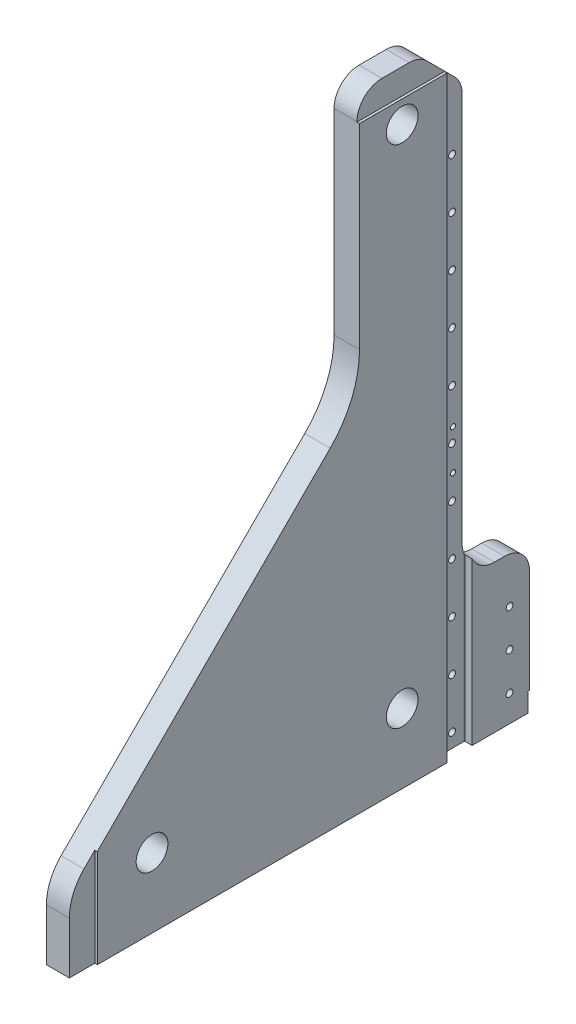
SolidWorks part; units mm, degrees
material "Low Carbon Steel"
ref_plane "Front Plane" through (0, 0, 0) normal (0, 0, 1) x (1, 0, 0)
ref_plane "Top Plane" through (0, 0, 0) normal (0, 1, 0) x (1, 0, 0)
ref_plane "Right Plane" through (0, 0, 0) normal (1, 0, 0) x (0, 0, -1)
sketch "Sketch1" plane through (0, 0, 0) normal (1, 0, 0) x (0, 0, -1)
  line L0 (0, 350) -> (0, 1129.2893)
  line L1 (-120.7107, 1250) -> (-175, 1250)
  line L2 (-225, 1200) -> (-225, 807.8427)
  line L3 (-283.5786, 666.4214) -> (-770.7107, 179.2893)
  line L4 (-800, 108.5786) -> (-800, 0)
  line L5 (-85.3553, 1235.3553) -> (-14.6447, 1164.6447)
  line L6 (0, 0) -> (120, 0)
  line L7 (-800, 0) -> (0, 0)
  line L9 (50, 300) -> (70, 300)
  line L10 (120, 0) -> (120, 250)
  arc A0 (-770.7107, 179.2893) -> (-800, 108.5786) centre (-700, 108.5786) ccw
  arc A1 (-225, 807.8427) -> (-283.5786, 666.4214) centre (-425, 807.8427) cw
  arc A2 (0, 350) -> (50, 300) centre (50, 350) ccw
  arc A3 (70, 300) -> (120, 250) centre (70, 250) cw
  arc A4 (-14.6447, 1164.6447) -> (0, 1129.2893) centre (-50, 1129.2893) cw
  arc A5 (-85.3553, 1235.3553) -> (-120.7107, 1250) centre (-120.7107, 1200) ccw
  arc A6 (-175, 1250) -> (-225, 1200) centre (-175, 1200) ccw
  point P8 (-800, 150)
  point P12 (-225, 725)
  point P18 (0, 300)
  point P21 (120, 300)
  point P27 (-100, 1250)
  dimension "D6" = 100
  dimension "D7" = 200
  dimension "D10" = 50
  dimension "D13" = 50
  dimension "D1" = 45
  dimension "D2" = 125
  dimension "D3" = 150
  dimension "D4" = 575
  dimension "D5" = 225
  dimension "D8" = 120
  dimension "D9" = 300
  dimension "D11" = 920
  dimension "D12" = 1250
extrude "Boss-Extrude1" add sketch "Sketch1" along normal blind 50.8
sketch "Sketch2" plane through (0, 1250, 0) normal (0, 1, 0) x (1, 0, 0)
  line L1 (30.8, 5) -> (50.8, 5)
  line L2 (30.8, 5) -> (30.8, -50)
  line L3 (30.8, -50) -> (50.8, -50)
  line L4 (50.8, 5) -> (50.8, -50)
  line L5 (50.8, -120.7107) -> (50.8, -175) construction
  line L6 (50.8, 0) -> (0, 0) construction
  dimension "D1" = 50
  dimension "D2" = 20
  dimension "D3" = 5
extrude "Cut-Extrude1" cut sketch "Sketch2" against normal through all
sketch "Sketch3" plane through (0, 0, 800) normal (0, 0, -1) x (-1, 0, 0)
  line L0 (-50.8, 0) -> (-50.8, 1200) construction
  line L1 (0, 0) -> (-50.8, 0)
  line L2 (0, 0) -> (0, 5)
  line L3 (0, 5) -> (-50.8, 5)
  line L4 (-50.8, 0) -> (-50.8, 5)
  dimension "D1" = 5
extrude "Cut-Extrude2" cut sketch "Sketch3" along normal through all
sketch "Sketch5" plane through (50.8, 0, 0) normal (1, 0, 0) x (0, 0, -1)
  line L1 (5, 328.2055) -> (120, 328.2055)
  line L2 (5, 328.2055) -> (5, 5)
  line L3 (5, 5) -> (120, 5)
  line L4 (120, 328.2055) -> (120, 5)
extrude "Cut-Extrude5" cut sketch "Sketch5" against normal offset from surface (5 mm away) 15 up to face at (30.8, 597.6161, 14.6232)
sketch "Sketch6" plane through (30.8, 0, 0) normal (1, 0, 0) x (0, 0, -1)
  line L0 (0, 1129.2893) -> (0, 350) construction
  line L1 (-185, 595) -> (0, 595)
  line L2 (-185, 595) -> (-185, 445)
  line L3 (-185, 445) -> (0, 445)
  line L4 (0, 595) -> (0, 445)
  line L6 (-50, 5) -> (-800, 5) construction
  line L7 (-50, 5) -> (-50, 1200) construction
  dimension "D1" = 150
  dimension "D2" = 135
  dimension "D3" = 440
extrude "Cut-Extrude6" cut sketch "Sketch6" against normal through all from offset 27 offset against normal yes
fillet "Fillet1" radius 38.1 2 edges at (1.9, 445, 185) (1.9, 595, 185)
hole_wizard "M12 Tapped Hole1" positions "Sketch8" profile "Sketch7" tap size "M12" standard "Peddi DIN"
sketch "Sketch8" plane through (3.8, 0, 0) normal (-1, 0, 0) x (0, 0, 1)
  line L0 (18, 561) -> (150, 561) construction
  line L1 (150, 561) -> (150, 481) construction
  line L2 (150, 481) -> (18, 481) construction
  line L3 (18, 481) -> (18, 561) construction
  line L6 (-120, 5) -> (800, 5) construction
  line L7 (50, 5) -> (50, 1200) construction
  point P0 (150, 561)
  point P2 (18, 561)
  point P4 (18, 481)
  point P6 (150, 481)
  dimension "D1" = 132
  dimension "D2" = 80
  dimension "D3" = 32
  dimension "D4" = 476
sketch "Sketch7" plane through (3.8, 561, 150) normal (0, 1, 0) x (0, 0, 1)
  line L0 (0, 0) -> (0, 47.0544)
  line L1 (0, 47.0544) -> (5.1, 43.99)
  line L2 (5.1, 43.99) -> (5.1, 0)
  line L5 (5.1, 0) -> (0, 0)
  line L10 (0, 47.0544) -> (-5.1, 43.99) construction
  line L11 (0, -6.35) -> (0, 107.95) construction
  dimension "Tap Drill Dia." = 10.2
  dimension "Tap Drill Depth" = 43.99
  dimension "Drill Angle" = 118
cosmetic thread "Hole Thread1" parameters "D1"=30, "D2"=12
cosmetic thread "Hole Thread2" parameters "D1"=27, "D2"=12
cosmetic thread "Hole Thread3" parameters "D1"=27, "D2"=12
cosmetic thread "Hole Thread4" parameters "D1"=30, "D2"=12
sketch "Sketch9" plane through (3.8, 0, 0) normal (-1, 0, 0) x (0, 0, 1)
  line L0 (89, 544) -> (89, 498) construction
  line L1 (95, 544) -> (95, 498)
  line L2 (83, 544) -> (83, 498)
  line L3 (18, 561) -> (18, 481) construction
  line L4 (18, 521) -> (89, 521) construction
  arc A0 (95, 544) -> (83, 544) centre (89, 544) ccw
  arc A1 (83, 498) -> (95, 498) centre (89, 498) ccw
  point P2 (89, 521)
  dimension "D1" = 12
  dimension "D2" = 65
  dimension "D3" = 46
extrude "Cut-Extrude7" cut sketch "Sketch9" against normal blind 5.08
hole_wizard "CBORE for M12 Hex Socket Head Cap Screw1" positions "Sketch10" profile "Sketch11" counterbore size "M12" standard "Peddi DIN" end condition through all
sketch "Sketch10" plane through (0, 0, 0) normal (-1, 0, 0) x (0, 0, 1)
  line L0 (50, 5) -> (50, 1200) construction
  line L2 (-120, 5) -> (800, 5) construction
  line L4 (-80, 58) -> (-80, 133) construction
  line L5 (-80, 133) -> (-80, 208) construction
  line L7 (20, 33) -> (20, 133) construction
  line L8 (20, 133) -> (20, 233) construction
  line L9 (20, 233) -> (20, 333) construction
  line L10 (20, 333) -> (20, 433) construction
  line L12 (20, 433) -> (20, 533) construction
  line L13 (20, 533) -> (20, 633) construction
  line L14 (20, 633) -> (20, 733) construction
  line L15 (20, 733) -> (20, 833) construction
  line L16 (20, 833) -> (20, 933) construction
  line L17 (20, 933) -> (20, 1033) construction
  line L18 (20, 133) -> (-80, 133) construction
  point P0 (20, 33)
  point P10 (-80, 58)
  point P20 (-80, 133)
  point P21 (-80, 208)
  point P26 (20, 133)
  point P28 (20, 233)
  point P30 (20, 333)
  point P32 (20, 433)
  point P39 (20, 533)
  point P41 (20, 633)
  point P42 (20, 733)
  point P44 (20, 833)
  point P46 (20, 933)
  point P48 (20, 1033)
  dimension "D4" = 75
  dimension "D1" = 30
  dimension "D2" = 28
  dimension "D3" = 100
  dimension "D5" = 100
sketch "Sketch11" plane through (0, 33, 20) normal (0, 1, 0) x (0, 0, 1)
  line L0 (0, 0) -> (0, 50.8)
  line L1 (0, 50.8) -> (6.75, 50.8)
  line L3 (6.75, 50.8) -> (6.75, 13)
  line L4 (6.75, 13) -> (10, 13)
  line L5 (10, 13) -> (10, 0)
  line L7 (10, 0) -> (0, 0)
  line L11 (0, -6.35) -> (0, 107.95) construction
  dimension "Thru Hole Dia." = 13.5
  dimension "Thru Hole Depth" = 50.8
  dimension "C'Bore Dia." = 20
  dimension "C'Bore Depth" = 13
hole_wizard "M12 Tapped Hole2" positions "Sketch14" profile "Sketch15" tap size "M12" standard "Peddi DIN"
sketch "Sketch14" plane through (0, 5, 0) normal (0, -1, 0) x (-1, 0, 0)
  line L1 (-45.8, 5) -> (-45.8, 120) construction
  line L2 (-25.8, 90) -> (-25.8, 30) construction
  line L3 (-25.8, 30) -> (-25.8, -60) construction
  line L4 (-25.8, -60) -> (-25.8, -140) construction
  line L5 (-25.8, -140) -> (-25.8, -220) construction
  line L6 (-25.8, -220) -> (-25.8, -300) construction
  line L9 (-25.8, -620) -> (-25.8, -710) construction
  line L10 (-25.8, -710) -> (-25.8, -770) construction
  line L11 (-25.8, -770) -> (-25.8, -800) construction
  line L13 (0, -800) -> (-50.8, -800) construction
  line L14 (-25.8, -300) -> (-25.8, -380) construction
  line L15 (-25.8, -380) -> (-25.8, -460) construction
  line L17 (-25.8, -460) -> (-25.8, -540) construction
  line L18 (-25.8, -540) -> (-25.8, -620) construction
  line L19 (-30.8, -50) -> (-50.8, -50) construction
  point P0 (-25.8, 90)
  point P48 (-25.8, 30)
  point P51 (-25.8, -60)
  point P54 (-25.8, -140)
  point P57 (-25.8, -220)
  point P62 (-25.8, -380)
  point P65 (-25.8, -300)
  point P68 (-25.8, -460)
  point P71 (-25.8, -540)
  point P74 (-25.8, -620)
  point P77 (-25.8, -710)
  point P80 (-25.8, -770)
  dimension "D1" = 140
  dimension "D2" = 20
  dimension "D3" = 60
  dimension "D4" = 90
  dimension "D5" = 80
sketch "Sketch15" plane through (25.8, 5, -90) normal (1, 0, 0) x (0, 0, -1)
  line L0 (0, 0) -> (0, 47.0544)
  line L1 (0, 47.0544) -> (5.1, 43.99)
  line L2 (5.1, 43.99) -> (5.1, 0)
  line L5 (5.1, 0) -> (0, 0)
  line L10 (0, 47.0544) -> (-5.1, 43.99) construction
  line L11 (0, -6.35) -> (0, 107.95) construction
  dimension "Tap Drill Dia." = 10.2
  dimension "Tap Drill Depth" = 43.99
  dimension "Drill Angle" = 118
cosmetic thread "Hole Thread5" parameters "D1"=30, "D2"=12
cosmetic thread "Hole Thread6" parameters "D1"=30, "D2"=12
cosmetic thread "Hole Thread7" parameters "D1"=30, "D2"=12
cosmetic thread "Hole Thread8" parameters "D1"=30, "D2"=12
cosmetic thread "Hole Thread9" parameters "D1"=30, "D2"=12
cosmetic thread "Hole Thread10" parameters "D1"=30, "D2"=12
cosmetic thread "Hole Thread11" parameters "D1"=30, "D2"=12
cosmetic thread "Hole Thread12" parameters "D1"=30, "D2"=12
cosmetic thread "Hole Thread13" parameters "D1"=30, "D2"=12
cosmetic thread "Hole Thread14" parameters "D1"=30, "D2"=12
cosmetic thread "Hole Thread15" parameters "D1"=30, "D2"=12
cosmetic thread "Hole Thread16" parameters "D1"=30, "D2"=12
fillet "Fillet2" radius 0.7937 4 edges at (8.88, 492, 89) (8.88, 521, 83) (8.88, 550, 89) (8.88, 521, 95)
fillet "Fillet3" radius 0.7937 2 edges at (30.8, 602.5, 50) (30.8, 166.6028, -5)
sketch "Sketch16" plane through (45.8, 0, 0) normal (1, 0, 0) x (0, 0, -1)
  line L0 (0, 1129.2893) -> (0, 350) construction
  line L1 (-225, 1250) -> (0, 1250)
  line L2 (-225, 1250) -> (-225, 1199.2)
  line L3 (-225, 1199.2) -> (0, 1199.2)
  line L4 (0, 1250) -> (0, 1199.2)
  line L5 (-283.5786, 666.4214) -> (-770.7107, 179.2893) construction
  line L6 (-800, 5) -> (-749.2, 5)
  line L7 (-800, 5) -> (-800, 200.8)
  line L8 (-800, 200.8) -> (-749.2, 200.8)
  line L9 (-749.2, 5) -> (-749.2, 200.8)
  line L10 (-225, 1200) -> (-225, 807.8427) construction
  line L11 (-120.7107, 1250) -> (-175, 1250) construction
  dimension "D1" = 50.8
  dimension "D2" = 50.8
extrude "Cut-Extrude8" cut sketch "Sketch16" along normal through all
sketch "Sketch17" plane through (50.8, 0, 0) normal (1, 0, 0) x (0, 0, -1)
  line L0 (120, 5) -> (120, 250) construction
  line L1 (120, 5) -> (116.825, 5)
  line L2 (120, 5) -> (120, 43.1)
  line L3 (120, 43.1) -> (116.825, 43.1)
  line L4 (116.825, 5) -> (116.825, 43.1)
  line L5 (-50, 5) -> (-749.2, 5) construction
  circle A0 centre (-139.6896, 144.2936) radius 31.75
  dimension "D3" = 63.5
  dimension "D1" = 3.175
  dimension "D2" = 38.1
  dimension "D4" = 259.6896
  dimension "D5" = 139.2936
extrude "Cut-Extrude9" cut sketch "Sketch17" against normal through all
sketch "Sketch18" plane through (50.8, 0, 0) normal (1, 0, 0) x (0, 0, -1)
  line L0 (-139.6896, 144.2936) -> (-139.6896, 1155) construction
  line L1 (-639.6896, 144.2936) -> (-139.6896, 144.2936) construction
  line L2 (-50, 5) -> (-749.2, 5) construction
  circle A0 centre (-639.6896, 144.2936) radius 31.75
  circle A1 centre (-139.6896, 1155) radius 31.75
  circle A2 centre (-139.6896, 144.2936) radius 31.75 construction
  dimension "D1" = 1150
  dimension "D2" = 500
extrude "Cut-Extrude10" cut sketch "Sketch18" against normal through all
other "Freeze***"
